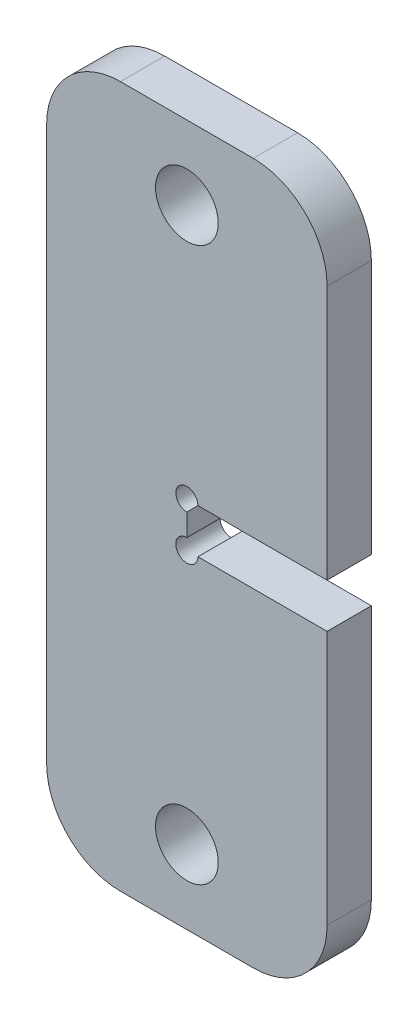
SolidWorks part; units mm, degrees
material "Plain Carbon Steel"
ref_plane "Front Plane" through (0, 0, 0) normal (0, 0, 1) x (1, 0, 0)
ref_plane "Top Plane" through (0, 0, 0) normal (0, 1, 0) x (1, 0, 0)
ref_plane "Right Plane" through (0, 0, 0) normal (1, 0, 0) x (0, 0, -1)
sketch "Sketch1" plane through (0, 0, 0) normal (0, 0, 1) x (1, 0, 0)
  line L0 (705, 423) -> (705, 328) construction
  line L1 (705, 375.5) -> (724, 375.5) construction
  line L2 (724, 378.5) -> (724, 413)
  line L3 (705, 378.5) -> (724, 378.5)
  line L4 (686, 413) -> (686, 338)
  line L5 (714, 423) -> (696, 423)
  line L6 (724, 338) -> (724, 413)
  line L7 (696, 328) -> (714, 328)
  line L8 (686, 413) -> (686, 338)
  line L9 (714, 423) -> (696, 423)
  line L10 (724, 338) -> (724, 372.5)
  line L11 (696, 328) -> (714, 328)
  line L12 (705, 378.5) -> (705, 372.5)
  line L13 (705, 372.5) -> (724, 372.5)
  line L15 (705, 378.5) -> (724, 372.5) construction
  line L16 (705, 372.5) -> (724, 378.5) construction
  circle A6 centre (705, 338) radius 4.25 construction
  circle A7 centre (705, 413) radius 4.25 construction
  arc A8 (696, 423) -> (686, 413) centre (696, 413) ccw
  arc A9 (724, 413) -> (714, 423) centre (714, 413) ccw
  arc A10 (714, 328) -> (724, 338) centre (714, 338) ccw
  arc A11 (686, 338) -> (696, 328) centre (696, 338) ccw
  arc A12 (696, 423) -> (686, 413) centre (696, 413) ccw
  arc A13 (724, 413) -> (714, 423) centre (714, 413) ccw
  arc A14 (714, 328) -> (724, 338) centre (714, 338) ccw
  arc A15 (686, 338) -> (696, 328) centre (696, 338) ccw
  circle A16 centre (705, 338) radius 4.25
  circle A17 centre (705, 413) radius 4.25
  point P10 (714.5, 375.5)
  dimension "D1" = 0
  dimension "D2" = 6
extrude "Boss-Extrude1" add sketch "Sketch1" along normal blind 6 from surface at 5
sketch "Sketch3" plane through (0, 0, 11) normal (0, 0, 1) x (1, 0, 0)
  line L0 (705, 372.5) -> (705, 378.5) construction
  line L1 (705, 378.5) -> (724, 378.5) construction
  circle A0 centre (705, 378.5) radius 1.5
  circle A1 centre (705, 372.5) radius 1.5
  dimension "D1" = 3
  dimension "D2" = 3
extrude "Cut-Extrude1" cut sketch "Sketch3" against normal through all
